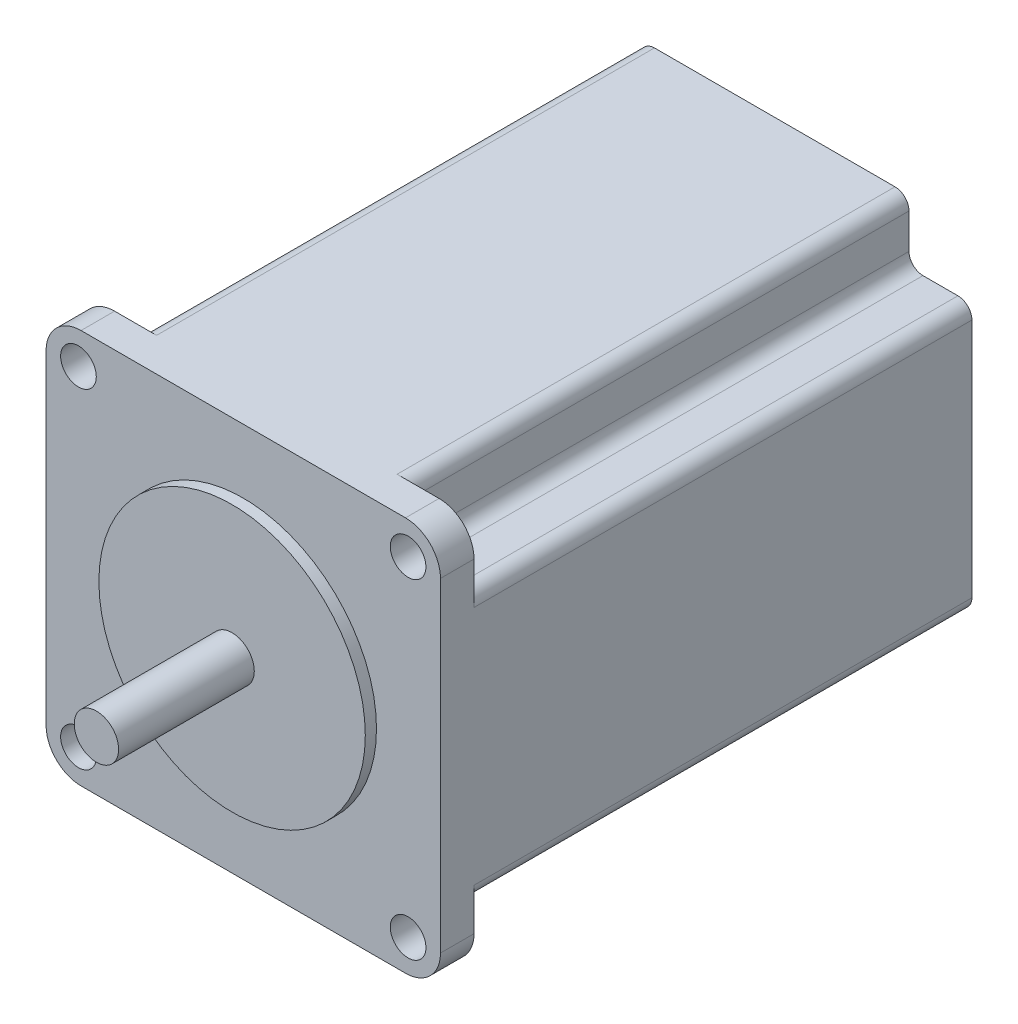
SolidWorks part; units mm, degrees
ref_plane "Спереди" through (0, 0, 0) normal (0, 0, 1) x (1, 0, 0)
ref_plane "Сверху" through (0, 0, 0) normal (0, 1, 0) x (1, 0, 0)
ref_plane "Справа" through (0, 0, 0) normal (1, 0, 0) x (0, 0, -1)
sketch "Эскиз1" plane through (0, 0, 0) normal (0, 0, 1) x (1, 0, 0)
  line L1 (5, 0) -> (51.4, 0)
  line L2 (0, 5) -> (0, 51.4)
  line L3 (5, 56.4) -> (51.4, 56.4)
  line L4 (56.4, 5) -> (56.4, 51.4)
  arc A0 (5, 0) -> (0, 5) centre (5, 5) cw
  arc A1 (51.4, 0) -> (56.4, 5) centre (51.4, 5) ccw
  arc A2 (51.4, 56.4) -> (56.4, 51.4) centre (51.4, 51.4) cw
  arc A3 (5, 56.4) -> (0, 51.4) centre (5, 51.4) ccw
  point P7 (0, 0)
  point P14 (0, 56.4)
  dimension "D3" = 5
  dimension "D1" = 56.4
  dimension "D2" = 56.4
extrude "Бобышка-Вытянуть1" add sketch "Эскиз1" along normal blind 76
sketch "Эскиз2" plane through (0, 0, 76) normal (0, 0, 1) x (1, 0, 0)
  line L0 (28.2, 28.2) -> (28.2, 0) construction
  line L1 (5, 0) -> (51.4, 0) construction
  line L2 (28.2, 28.2) -> (56.4, 28.2) construction
  line L3 (56.4, 5) -> (56.4, 51.4) construction
  circle A0 centre (28.2, 28.2) radius 19.05
  dimension "D1" = 38.1
extrude "Бобышка-Вытянуть2" add sketch "Эскиз2" along normal blind 1.6
sketch "Эскиз3" plane through (0, 0, 0) normal (0, 0, -1) x (-1, 0, 0)
  line L0 (-56.4, 11) -> (-56.4, 45.4)
  line L1 (-56.4, 5) -> (-56.4, 51.4) construction
  line L2 (-54.4, 47.4) -> (-49.4, 47.4)
  line L3 (-47.4, 49.4) -> (-47.4, 54.4)
  line L4 (-45.4, 56.4) -> (-11, 56.4)
  line L5 (-51.4, 56.4) -> (-5, 56.4) construction
  line L6 (-28.2, 56.4) -> (-28.2, 28.2) construction
  line L7 (-28.2, 28.2) -> (-56.4, 28.2) construction
  line L8 (0, 11) -> (0, 45.4)
  line L9 (-9, 49.4) -> (-9, 54.4)
  line L10 (-2, 47.4) -> (-7, 47.4)
  line L11 (-2, 9) -> (-7, 9)
  line L12 (-9, 7) -> (-9, 2)
  line L13 (-45.4, 0) -> (-11, 0)
  line L14 (-47.4, 7) -> (-47.4, 2)
  line L15 (-54.4, 9) -> (-49.4, 9)
  circle A0 centre (-51.77, 51.77) radius 2.55 construction
  arc A1 (-45.4, 56.4) -> (-47.4, 54.4) centre (-45.4, 54.4) ccw
  arc A2 (-47.4, 49.4) -> (-49.4, 47.4) centre (-49.4, 49.4) cw
  arc A3 (-54.4, 47.4) -> (-56.4, 45.4) centre (-54.4, 45.4) ccw
  circle A4 centre (-4.63, 51.77) radius 2.55 construction
  arc A5 (-2, 47.4) -> (0, 45.4) centre (-2, 45.4) cw
  arc A6 (-9, 49.4) -> (-7, 47.4) centre (-7, 49.4) ccw
  arc A7 (-11, 56.4) -> (-9, 54.4) centre (-11, 54.4) cw
  circle A8 centre (-4.63, 4.63) radius 2.55 construction
  circle A9 centre (-51.77, 4.63) radius 2.55 construction
  arc A10 (-11, 0) -> (-9, 2) centre (-11, 2) ccw
  arc A11 (-9, 7) -> (-7, 9) centre (-7, 7) cw
  arc A12 (-2, 9) -> (0, 11) centre (-2, 11) ccw
  arc A13 (-54.4, 9) -> (-56.4, 11) centre (-54.4, 11) cw
  arc A14 (-47.4, 7) -> (-49.4, 9) centre (-49.4, 7) ccw
  arc A15 (-45.4, 0) -> (-47.4, 2) centre (-45.4, 2) cw
  point P55 (0, 28.2)
  dimension "D1" = 47.14
  dimension "D2" = 47.14
  dimension "D3" = 5.1
  dimension "D4" = 2
  dimension "D5" = 9
extrude "Вырез-Вытянуть1" cut sketch "Эскиз3" against normal blind 71.2 flip side to cut
sketch "Эскиз4" plane through (0, 0, 76) normal (0, 0, 1) x (1, 0, 0)
  line L0 (28.2, 56.4) -> (28.2, 28.2) construction
  line L1 (51.4, 56.4) -> (5, 56.4) construction
  line L2 (28.2, 28.2) -> (0, 28.2) construction
  line L3 (0, 51.4) -> (0, 5) construction
  circle A0 centre (4.63, 51.77) radius 2.55
  circle A1 centre (51.77, 51.77) radius 2.55
  circle A2 centre (4.63, 4.63) radius 2.55
  circle A3 centre (51.77, 4.63) radius 2.55
  dimension "D1" = 5.1
  dimension "D2" = 47.14
  dimension "D3" = 47.14
extrude "Вырез-Вытянуть2" cut sketch "Эскиз4" against normal blind 71.2
sketch "Эскиз5" plane through (0, 0, 77.6) normal (0, 0, 1) x (1, 0, 0)
  circle A0 centre (28.2, 28.2) radius 3.175
  circle A1 centre (28.2, 28.2) radius 19.05 construction
  dimension "D1" = 6.35
extrude "Бобышка-Вытянуть3" add sketch "Эскиз5" along normal blind 19.4
